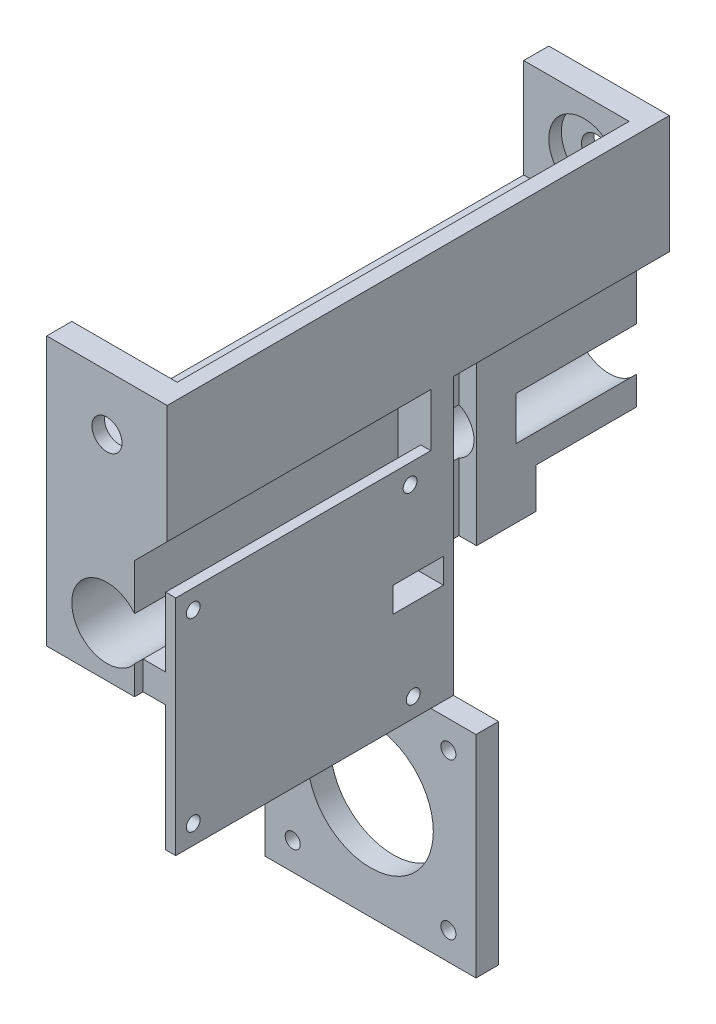
SolidWorks part; units mm, degrees
ref_plane "Front Plane" through (0, 0, 0) normal (0, 0, 1) x (1, 0, 0)
ref_plane "Top Plane" through (0, 0, 0) normal (0, 1, 0) x (1, 0, 0)
ref_plane "Right Plane" through (0, 0, 0) normal (1, 0, 0) x (0, 0, -1)
sketch "Sketch1" plane through (0, 0, 0) normal (0, 0, 1) x (1, 0, 0)
  line L0 (-12, 7) -> (9, 7)
  line L1 (-12, 26.75) -> (12, 26.75) construction
  line L2 (-12, 26.75) -> (-12, -26.75) construction
  line L3 (-12, -26.75) -> (12, -26.75)
  line L4 (12, 26.75) -> (12, -26.75)
  line L5 (-12, 26.75) -> (12, -26.75) construction
  line L6 (-12, -26.75) -> (12, 26.75) construction
  line L7 (9, 7) -> (9, 26.75)
  line L8 (9, 26.75) -> (12, 26.75)
  line L9 (-12, 7) -> (-12, -26.75)
  line L10 (-12, 7.75) -> (-12, 6.25) construction
  circle A0 centre (0, -16.75) radius 7
  circle A1 centre (-12, -0.75) radius 7 construction
  circle A2 centre (-12, 15.75) radius 8 construction
  point P2 (-7, -16.75)
  point P4 (0, 0)
  point P9 (0, -23.75)
  point P14 (-12, 7.75)
  point P15 (0, -9.75)
  point P16 (-12, -7.75)
  point P17 (-12, 23.75)
  dimension "D1" = 14
  dimension "D5" = 16
  dimension "D2" = 5
  dimension "D3" = 3
  dimension "D4" = 8.5
  dimension "D6" = 2
  dimension "D7" = 3
  dimension "D8" = 3
extrude "Boss-Extrude1" add sketch "Sketch1" along normal mid plane 100
sketch "Sketch2" plane through (-12, 0, 0) normal (-1, 0, 0) x (0, 0, 1)
  line L0 (-24.1, -0.75) -> (24.1, -0.75) construction
  circle A0 centre (-24.1, -0.75) radius 4
  circle A1 centre (24.1, -0.75) radius 4
  point P0 (0, -0.75)
  dimension "D2" = 8
  dimension "D1" = 48.2
extrude "Cut-Extrude1" cut sketch "Sketch2" against normal offset from surface (17 mm away) 7 up to face at (12, 0, 0)
sketch "Sketch3" plane through (9, 0, 0) normal (-1, 0, 0) x (0, 0, 1)
  line L0 (50, 7) -> (-50, 7) construction
  line L1 (-50, 26.75) -> (-45, 26.75)
  line L2 (-50, 26.75) -> (-50, 7)
  line L3 (-50, 7) -> (-45, 7)
  line L4 (-45, 26.75) -> (-45, 7)
  line L6 (50, 26.75) -> (45, 26.75)
  line L7 (50, 26.75) -> (50, 7)
  line L8 (50, 7) -> (45, 7)
  line L9 (45, 26.75) -> (45, 7)
  dimension "D1" = 5
extrude "Boss-Extrude2" add sketch "Sketch3" along normal through all
sketch "Sketch4" plane through (0, 0, 0) normal (0, 0, 1) x (1, 0, 0)
  circle A0 centre (0, 15.75) radius 7
  dimension "D1" = 14
extrude "Cut-Extrude4" cut sketch "Sketch4" against normal mid plane 95
sketch "Sketch6" plane through (0, 0, 0) normal (0, 0, 1) x (1, 0, 0)
  circle A0 centre (0, -16.75) radius 5
  circle A1 centre (0, -16.75) radius 7 construction
  circle A2 centre (0, -16.75) radius 7
  dimension "D1" = 10
extrude "Boss-Extrude3" add sketch "Sketch6" along normal mid plane 52
sketch "Sketch7" plane through (-12, 0, 0) normal (-1, 0, 0) x (0, 0, 1)
  line L0 (-35, -16.75) -> (35, -16.75) construction
  circle A0 centre (-35, -16.75) radius 1
  circle A1 centre (35, -16.75) radius 1
  dimension "D1" = 2
  dimension "D2" = 70
extrude "Cut-Extrude5" cut sketch "Sketch7" against normal up to next
sketch "Sketch8" plane through (0, 0, 47.5) normal (0, 0, -1) x (-1, 0, 0)
  circle A0 centre (0, 15.75) radius 3
  dimension "D1" = 6
extrude "Cut-Extrude6" cut sketch "Sketch8" against normal through all both and the other way through all
sketch "Sketch9" plane through (0, 0, 50) normal (0, 0, 1) x (1, 0, 0)
  line L0 (5.5, -3.25) -> (12, 3.25)
  line L1 (12, -26.75) -> (5.5, -26.75)
  line L2 (12, -26.75) -> (12, 3.25)
  line L4 (5.5, -26.75) -> (5.5, -3.25)
  circle A0 centre (0, -16.75) radius 7 construction
  circle A1 centre (0, -16.75) radius 7 construction
  point P5 (7, -16.75)
  dimension "D1" = 1.5
  dimension "D2" = 30
  dimension "D3" = 45
extrude "Cut-Extrude7" cut sketch "Sketch9" against normal through all
sketch "Sketch10" plane through (-12, 0, 0) normal (-1, 0, 0) x (0, 0, 1)
  line L0 (-5, -26.75) -> (-5, -31.75)
  line L1 (50, -26.75) -> (-50, -26.75) construction
  line L2 (-5, -31.75) -> (5, -31.75)
  line L3 (5, -31.75) -> (5, -26.75)
  line L4 (5, -26.75) -> (30, -26.75)
  line L5 (30, -26.75) -> (30, -34.75)
  line L6 (30, -34.75) -> (-30, -34.75)
  line L7 (-30, -34.75) -> (-30, -26.75)
  line L8 (-30, -26.75) -> (-5, -26.75)
  line L9 (-50, 26.75) -> (-50, -26.75) construction
  point P15 (0, -31.75)
  dimension "D1" = 5
  dimension "D2" = 3
  dimension "D3" = 10
  dimension "D4" = 20
extrude "Boss-Extrude4" add sketch "Sketch10" against normal up to surface (17.5 mm away) up to face at (5.5, -16.1667, 0)
sketch "Sketch11" plane through (0, -31.75, 0) normal (0, 1, 0) x (1, 0, 0)
  line L0 (0, 2.5) -> (-12, 2.5)
  line L1 (-12, -5) -> (-12, 5) construction
  line L2 (-12, 2.5) -> (-12, -2.5)
  line L3 (-12, -2.5) -> (0, -2.5)
  line L5 (-5, -26) -> (5, -26) construction
  line L6 (-5, -26) -> (5, -26) construction
  arc A0 (0, 2.5) -> (0, -2.5) centre (0, 0) cw
  point P16 (0, -26)
  dimension "D1" = 5
extrude "Cut-Extrude8" cut sketch "Sketch11" against normal through all
sketch "Sketch12" plane through (0, 7, 0) normal (0, 1, 0) x (1, 0, 0)
  line L0 (2, 12.55) -> (-2, 12.55) construction
  line L1 (2, 18.1) -> (7, 18.1)
  line L2 (2, 18.1) -> (2, 7)
  line L3 (2, 7) -> (7, 7)
  line L4 (7, 18.1) -> (7, 7)
  line L5 (-2, 18.1) -> (-7, 18.1)
  line L6 (-2, 18.1) -> (-2, 7)
  line L7 (-2, 7) -> (-7, 7)
  line L8 (-7, 18.1) -> (-7, 7)
  line L9 (-12, 20.1) -> (5, 20.1) construction
  line L10 (5.5, 5) -> (-12, 5) construction
  point P10 (0, 12.55)
  dimension "D1" = 2
  dimension "D2" = 2
  dimension "D3" = 4
  dimension "D4" = 14
extrude "Cut-Extrude9" cut sketch "Sketch12" against normal through all
sketch "Sketch13" plane through (0, -34.75, 0) normal (0, -1, 0) x (1, 0, 0)
  line L12 (5.5, -7) -> (12, -7)
  line L13 (12, -50) -> (12, 50) construction
  line L14 (12, -7) -> (12, -2.5)
  line L15 (12, -2.5) -> (5.5, -2.5)
  line L16 (5.5, 30) -> (5.5, -7) construction
  line L17 (5.5, -2.5) -> (5.5, -7)
  line L18 (0, -2.5) -> (-12, -2.5) construction
extrude "Boss-Extrude5" add sketch "Sketch13" against normal up to next
sketch "Sketch14" plane through (5.5, 0, 0) normal (-1, 0, 0) x (0, 0, 1)
  line L4 (-2.5, -26.75) -> (-5, -26.75)
  line L5 (-5, -26.75) -> (-5, -31.75)
  line L6 (-5, -31.75) -> (-2.5, -31.75)
  line L7 (-2.5, -31.75) -> (-2.5, -26.75)
  line L12 (-2.5, -26.75) -> (-5, -26.75)
  line L13 (-5, -26.75) -> (-5, -31.75)
  line L14 (-5, -31.75) -> (-2.5, -31.75)
  line L15 (-2.5, -31.75) -> (-2.5, -26.75)
  dimension "D1" = 0
extrude "Cut-Extrude10" cut sketch "Sketch14" against normal through all
sketch "Sketch16" plane through (0, 0, -7) normal (0, 0, -1) x (-1, 0, 0)
  line L0 (-12, -34.75) -> (-5, -34.75)
  line L1 (-2, -34.75) -> (-12, -34.75) construction
  line L2 (-5, -34.75) -> (-5, -49.75)
  line L3 (-5, -49.75) -> (5, -49.75)
  line L4 (5, -49.75) -> (5, -34.75)
  line L5 (-5.5, -34.75) -> (12, -34.75) construction
  line L6 (5, -34.75) -> (12, -34.75)
  line L7 (12, -34.75) -> (12, -51.75)
  line L9 (-12, -51.75) -> (-12, -34.75)
  line L10 (-12, -51.75) -> (-21, -51.75)
  line L11 (-21, -51.75) -> (-21, -93.75)
  line L12 (-21, -93.75) -> (21, -93.75)
  line L13 (21, -93.75) -> (21, -51.75)
  line L14 (21, -51.75) -> (12, -51.75)
  line L16 (-15.5, -88.25) -> (15.5, -88.25) construction
  line L17 (-15.5, -88.25) -> (-15.5, -57.25) construction
  line L18 (-15.5, -57.25) -> (15.5, -57.25) construction
  line L19 (15.5, -88.25) -> (15.5, -57.25) construction
  line L20 (-15.5, -88.25) -> (15.5, -57.25) construction
  line L21 (-15.5, -57.25) -> (15.5, -88.25) construction
  circle A0 centre (0, -72.75) radius 12.5
  circle A1 centre (-15.5, -57.25) radius 1.5
  circle A2 centre (15.5, -57.25) radius 1.5
  circle A3 centre (15.5, -88.25) radius 1.5
  circle A4 centre (-15.5, -88.25) radius 1.5
  point P20 (-21, -72.75)
  point P21 (0, -93.75)
  point P30 (0, 0)
  dimension "D5" = 25
  dimension "D7" = 3
  dimension "D1" = 10
  dimension "D2" = 15
  dimension "D3" = 2
  dimension "D4" = 42
  dimension "D6" = 31
extrude "Boss-Extrude8" add sketch "Sketch16" against normal up to surface (4.5 mm away) up to face at (8.75, -13.375, -2.5)
sketch "Sketch18" plane through (12, 0, 0) normal (1, 0, 0) x (0, 0, -1)
  line L0 (2.5, -51.75) -> (-48.3, -51.75)
  line L1 (2.5, -51.75) -> (2.5, -31.75)
  line L2 (2.5, -31.75) -> (-5, -31.75)
  line L3 (-5, -31.75) -> (-5, -26.75)
  line L4 (-5, -26.75) -> (2.5, -26.75)
  line L5 (2.5, -26.75) -> (2.5, -7.3)
  line L6 (2.5, -3.25) -> (2.5, -26.75) construction
  line L7 (2.5, -7.3) -> (-48.3, -7.3)
  line L8 (-48.3, -7.3) -> (-48.3, -51.75)
  line L10 (-44.81, -47.94) -> (-0.99, -47.94) construction
  line L11 (-44.81, -47.94) -> (-44.81, -11.11) construction
  line L12 (-44.81, -11.11) -> (-0.99, -11.11) construction
  line L13 (-0.99, -47.94) -> (-0.99, -11.11) construction
  line L14 (-44.81, -47.94) -> (-0.99, -11.11) construction
  line L15 (-44.81, -11.11) -> (-0.99, -47.94) construction
  circle A0 centre (-44.81, -11.11) radius 1.375
  circle A2 centre (-0.99, -47.94) radius 1.375
  circle A3 centre (-44.81, -47.94) radius 1.375
  circle A4 centre (-1.63, -11.11) radius 1.375
  point P15 (-22.9, -29.525)
  point P21 (-48.3, -29.525)
  point P23 (-22.9, -51.75)
  dimension "D5" = 2.75
  dimension "D1" = 50.8
  dimension "D2" = 44.45
  dimension "D3" = 43.82
  dimension "D4" = 36.83
  dimension "D6" = 0.64
extrude "Boss-Extrude9" add sketch "Sketch18" against normal blind 2
sketch "Sketch20" plane through (10, 0, 0) normal (-1, 0, 0) x (0, 0, 1)
  line L0 (-2.5, -31.75) -> (-2.5, -34.75)
  line L1 (-2.5, -51.75) -> (-2.5, -31.75) construction
  line L3 (48.3, -7.3) -> (48.3, -51.75) construction
  line L5 (48.3, -21.0801) -> (-2.5, -21.0801)
  line L6 (-2.5, -21.0801) -> (-2.5, -26.75)
  line L7 (-2.5, -26.75) -> (5, -26.75)
  line L8 (5, -26.75) -> (5, -31.75)
  line L9 (5, -31.75) -> (-2.5, -31.75)
  line L10 (48.3, -21.0801) -> (48.3, -26.75)
  line L11 (48.3, -26.75) -> (30, -26.75)
  line L12 (30, -26.75) -> (30, -34.75)
  line L13 (30, -34.75) -> (-2.5, -34.75)
  point P18 (0, 0)
extrude "Boss-Extrude10" add sketch "Sketch20" along normal up to next
